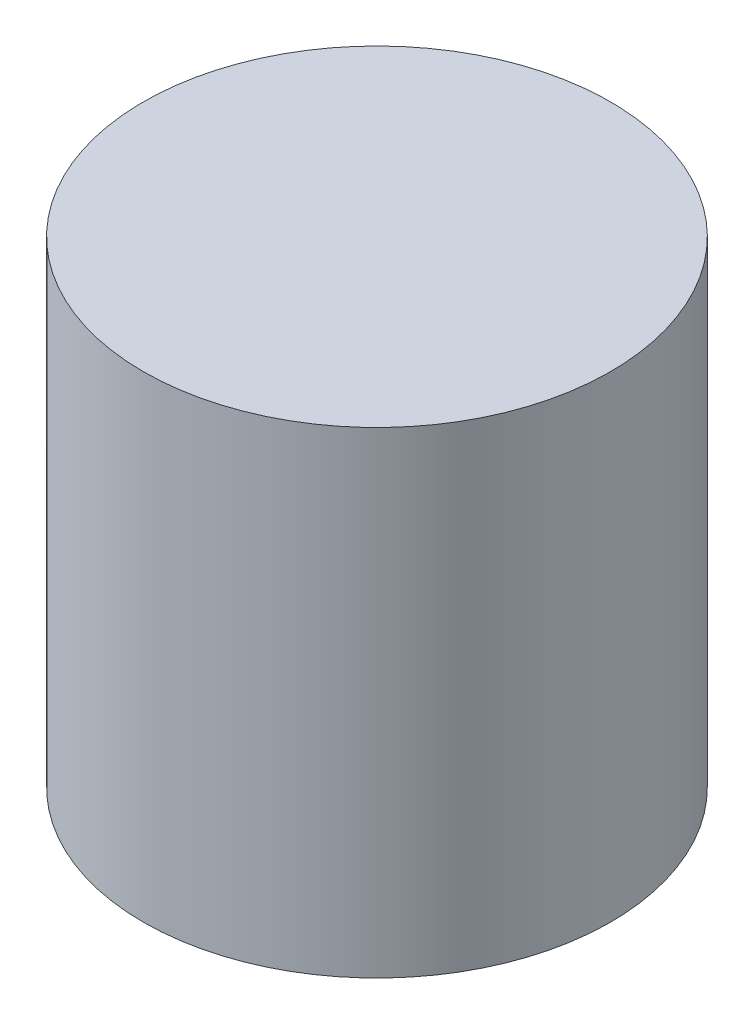
SolidWorks part; units mm, degrees
ref_plane "Front Plane" through (0, 0, 0) normal (0, 0, 1) x (1, 0, 0)
ref_plane "Top Plane" through (0, 0, 0) normal (0, 1, 0) x (1, 0, 0)
ref_plane "Right Plane" through (0, 0, 0) normal (1, 0, 0) x (0, 0, -1)
sketch "Sketch1" plane through (0, 0, 0) normal (0, 1, 0) x (1, 0, 0)
  circle A0 centre (0, 0) radius 4.9
  dimension "D1" = 9.8
extrude "Boss-Extrude1" add sketch "Sketch1" along normal blind 10
